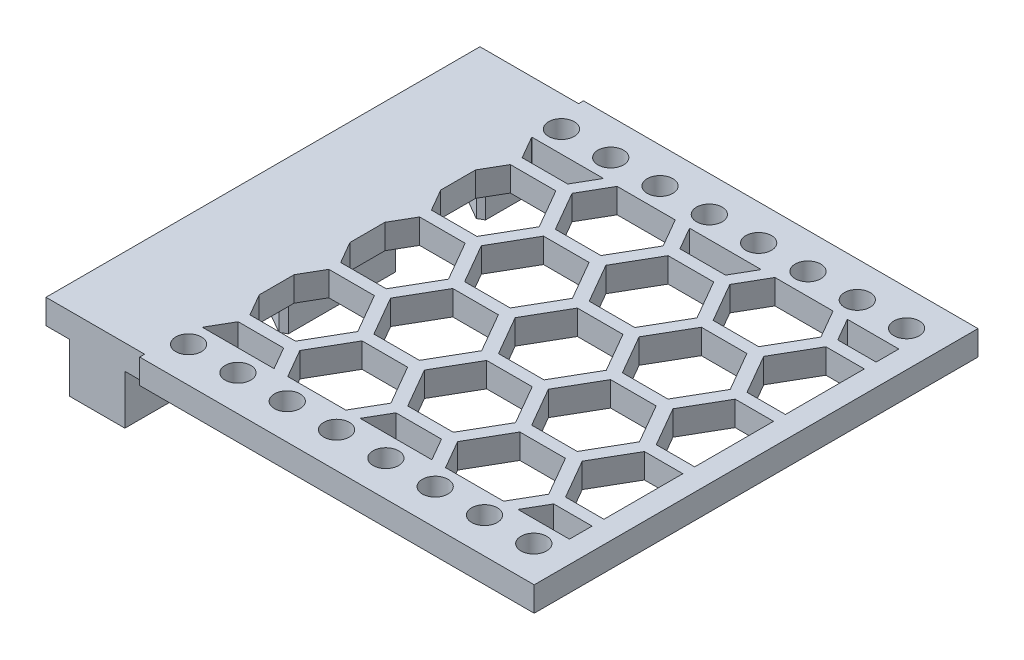
SolidWorks part; units mm, degrees
material "ABS PC"
ref_plane "Front Plane" through (0, 0, 0) normal (0, 0, 1) x (1, 0, 0)
ref_plane "Top Plane" through (0, 0, 0) normal (0, 1, 0) x (1, 0, 0)
ref_plane "Right Plane" through (0, 0, 0) normal (1, 0, 0) x (0, 0, -1)
sketch "Sketch1" plane through (0, 0, 0) normal (0, 1, 0) x (1, 0, 0)
  line L0 (0, 0) -> (-27.94, 0) construction
  line L1 (25.4, -28.575) -> (-25.4, -28.575)
  line L2 (25.4, -28.575) -> (25.4, 28.575)
  line L3 (25.4, 28.575) -> (-25.4, 28.575)
  line L4 (-25.4, -28.575) -> (-25.4, 28.575)
  line L5 (25.4, -28.575) -> (-25.4, 28.575) construction
  line L6 (25.4, 28.575) -> (-25.4, -28.575) construction
  line L7 (-38.1, -27.94) -> (-25.4, -27.94)
  line L8 (-38.1, -27.94) -> (-38.1, 27.94)
  line L9 (-38.1, 27.94) -> (-25.4, 27.94)
  line L10 (-25.4, -27.94) -> (-25.4, 27.94)
  line L11 (-27.94, -27.94) -> (-27.94, 27.94)
  point P0 (0, 0)
  point P11 (-38.1, 27.2937)
  point P12 (0, 0)
  point P13 (-38.1, 0)
  dimension "D1" = 57.15
  dimension "D2" = 50.8
  dimension "D3" = 55.88
  dimension "D4" = 12.7
  dimension "D7" = 2.54
extrude "Boss-Extrude1" add sketch "Sketch1" along normal blind 3.175 contours L4 L1 L2 L3 | L11 L7 L10 L4 L9 | L7 L11 L9 L8
sketch "Sketch2" plane through (0, 0, 0) normal (0, -1, 0) x (1, 0, 0)
  line L0 (-38.1, 27.94) -> (-38.1, -27.94) construction
  line L1 (-27.94, 6.8924) -> (-28.702, 7.3323)
  line L2 (-28.702, 7.3323) -> (-35.052, 3.6662)
  line L3 (-35.052, 3.6662) -> (-35.052, -3.6662)
  line L4 (-35.052, -3.6662) -> (-28.702, -7.3323)
  line L5 (-28.702, -7.3323) -> (-27.94, -6.8924)
  line L8 (-35.052, 27.94) -> (-35.052, 21.7338)
  line L10 (-35.052, 21.7338) -> (-28.702, 18.0677)
  line L11 (-27.94, -6.8924) -> (-27.94, 6.8924)
  line L12 (-22.352, 0) -> (-22.352, 3.6662) [skipped]
  line L13 (-28.702, 18.0677) -> (-27.94, 18.5076)
  line L14 (0, 0) -> (-38.1, 0) construction
  line L15 (-27.94, 18.5076) -> (-27.94, 27.94)
  line L17 (-27.94, -18.5076) -> (-27.94, -27.94)
  line L18 (-28.702, -18.0677) -> (-27.94, -18.5076)
  line L19 (-35.052, -21.7338) -> (-28.702, -18.0677)
  line L20 (-35.052, -27.94) -> (-35.052, -21.7338)
  line L23 (-27.94, -27.94) -> (-35.052, -27.94)
  line L24 (-35.052, 27.94) -> (-27.94, 27.94)
  line L37 (-28.702, 32.7323) -> (-35.052, 29.0662) [skipped]
  line L38 (-27.94, 32.2924) -> (-28.702, 32.7323) [skipped]
  line L39 (0, 25.4) -> (-27.94, 25.4) construction
  arc A0 (-27.94, 6.3041) -> (-27.94, -6.3041) centre (-28.702, 0) ccw construction
  arc A2 (-34.5219, -27.94) -> (-27.94, -19.0959) centre (-28.702, -25.4) cw construction
  arc A3 (-34.5219, 27.94) -> (-27.94, 19.0959) centre (-28.702, 25.4) ccw construction
  arc A5 (-27.94, 31.7041) -> (-31.877, 30.8993) centre (-28.702, 25.4) ccw construction
  dimension "D1" = 12.7
  dimension "D2" = 2
extrude "Boss-Extrude2" add sketch "Sketch2" along normal blind 6.35
sketch "Sketch3" plane through (0, 3.175, 0) normal (0, 1, 0) x (1, 0, 0)
  line L0 (25.4, -28.575) -> (-25.4, -28.575) construction
  line L1 (25.4, -28.575) -> (25.4, 28.575) construction
  line L2 (0, 0) -> (25.4, 0) construction
  circle A0 centre (20.7772, -24.003) radius 1.651
  circle A1 centre (14.4272, -24.003) radius 1.651
  circle A2 centre (8.0772, -24.003) radius 1.651
  circle A3 centre (1.7272, -24.003) radius 1.651
  circle A4 centre (-4.6228, -24.003) radius 1.651
  circle A5 centre (-10.9728, -24.003) radius 1.651
  circle A6 centre (-17.3228, -24.003) radius 1.651
  circle A7 centre (-23.6728, -24.003) radius 1.651
  circle A8 centre (-23.6728, 24.003) radius 1.651
  circle A9 centre (-17.3228, 24.003) radius 1.651
  circle A10 centre (-10.9728, 24.003) radius 1.651
  circle A11 centre (-4.6228, 24.003) radius 1.651
  circle A12 centre (1.7272, 24.003) radius 1.651
  circle A13 centre (8.0772, 24.003) radius 1.651
  circle A14 centre (14.4272, 24.003) radius 1.651
  circle A15 centre (20.7772, 24.003) radius 1.651
  dimension "D1" = 4.572
  dimension "D2" = 4.6228
  dimension "D4" = 3.302
  dimension "D3" = 8
extrude "Cut-Extrude1" cut sketch "Sketch3" against normal through all
sketch "Sketch4" plane through (0, 3.175, 0) normal (0, 1, 0) x (1, 0, 0)
  line L0 (26.4338, -0.0088) -> (23.5009, 5.0712)
  line L1 (6.1138, -0.0088) -> (3.1809, 5.0712)
  line L2 (3.1809, 5.0712) -> (-2.685, 5.0712)
  line L3 (-2.685, 5.0712) -> (-5.6179, -0.0088)
  line L4 (-5.6179, -0.0088) -> (-2.685, -5.0888)
  line L5 (-2.685, -5.0888) -> (3.1809, -5.0888)
  line L6 (3.1809, -5.0888) -> (6.1138, -0.0088)
  line L7 (23.5009, 5.0712) -> (17.635, 5.0712)
  line L8 (17.635, 5.0712) -> (14.7021, -0.0088)
  line L9 (14.7021, -0.0088) -> (17.635, -5.0888)
  line L10 (17.635, -5.0888) -> (23.5009, -5.0888)
  line L11 (23.5009, -5.0888) -> (26.4338, -0.0088)
  line L12 (26.4338, 11.6752) -> (23.5009, 16.7552)
  line L13 (23.5009, 16.7552) -> (17.635, 16.7552)
  line L14 (17.635, 16.7552) -> (14.7021, 11.6752)
  line L15 (14.7021, 11.6752) -> (17.635, 6.5952)
  line L16 (17.635, 6.5952) -> (23.5009, 6.5952)
  line L17 (23.5009, 6.5952) -> (26.4338, 11.6752)
  line L18 (26.4338, 23.3592) -> (23.5009, 28.4392)
  line L19 (23.5009, 28.4392) -> (17.635, 28.4392)
  line L20 (17.635, 28.4392) -> (14.7021, 23.3592)
  line L21 (14.7021, 23.3592) -> (17.635, 18.2792)
  line L22 (17.635, 18.2792) -> (23.5009, 18.2792)
  line L23 (23.5009, 18.2792) -> (26.4338, 23.3592)
  line L24 (6.1138, 11.6752) -> (3.1809, 16.7552)
  line L25 (3.1809, 16.7552) -> (-2.685, 16.7552)
  line L26 (-2.685, 16.7552) -> (-5.6179, 11.6752)
  line L27 (-5.6179, 11.6752) -> (-2.685, 6.5952)
  line L28 (-2.685, 6.5952) -> (3.1809, 6.5952)
  line L29 (3.1809, 6.5952) -> (6.1138, 11.6752)
  line L30 (6.1138, 23.3592) -> (3.1809, 28.4392)
  line L31 (3.1809, 28.4392) -> (-2.685, 28.4392)
  line L32 (-2.685, 28.4392) -> (-5.6179, 23.3592)
  line L33 (-5.6179, 23.3592) -> (-2.685, 18.2792)
  line L34 (-2.685, 18.2792) -> (3.1809, 18.2792)
  line L35 (3.1809, 18.2792) -> (6.1138, 23.3592)
  line L36 (-14.2062, -0.0088) -> (-17.1391, 5.0712)
  line L37 (-17.1391, 5.0712) -> (-23.005, 5.0712)
  line L38 (-23.005, 5.0712) -> (-25.9379, -0.0088)
  line L39 (-25.9379, -0.0088) -> (-23.005, -5.0888)
  line L40 (-23.005, -5.0888) -> (-17.1391, -5.0888)
  line L41 (-17.1391, -5.0888) -> (-14.2062, -0.0088)
  line L42 (-14.2062, -11.6928) -> (-17.1391, -6.6128)
  line L43 (-17.1391, -6.6128) -> (-23.005, -6.6128)
  line L44 (-23.005, -6.6128) -> (-25.9379, -11.6928)
  line L45 (-25.9379, -11.6928) -> (-23.005, -16.7728)
  line L46 (-23.005, -16.7728) -> (-17.1391, -16.7728)
  line L47 (-17.1391, -16.7728) -> (-14.2062, -11.6928)
  line L48 (-14.2062, -23.3768) -> (-17.1391, -18.2968)
  line L49 (-17.1391, -18.2968) -> (-23.005, -18.2968)
  line L50 (-23.005, -18.2968) -> (-25.9379, -23.3768)
  line L51 (-25.9379, -23.3768) -> (-23.005, -28.4568)
  line L52 (-23.005, -28.4568) -> (-17.1391, -28.4568)
  line L53 (-17.1391, -28.4568) -> (-14.2062, -23.3768)
  line L54 (6.1138, -11.6928) -> (3.1809, -6.6128)
  line L55 (3.1809, -6.6128) -> (-2.685, -6.6128)
  line L56 (-2.685, -6.6128) -> (-5.6179, -11.6928)
  line L57 (-5.6179, -11.6928) -> (-2.685, -16.7728)
  line L58 (-2.685, -16.7728) -> (3.1809, -16.7728)
  line L59 (3.1809, -16.7728) -> (6.1138, -11.6928)
  line L60 (6.1138, -23.3768) -> (3.1809, -18.2968)
  line L61 (3.1809, -18.2968) -> (-2.685, -18.2968)
  line L62 (-2.685, -18.2968) -> (-5.6179, -23.3768)
  line L63 (-5.6179, -23.3768) -> (-2.685, -28.4568)
  line L64 (-2.685, -28.4568) -> (3.1809, -28.4568)
  line L65 (3.1809, -28.4568) -> (6.1138, -23.3768)
  line L66 (-14.2062, 11.6752) -> (-17.1391, 16.7552)
  line L67 (-17.1391, 16.7552) -> (-23.005, 16.7552)
  line L68 (-23.005, 16.7552) -> (-25.9379, 11.6752)
  line L69 (-25.9379, 11.6752) -> (-23.005, 6.5952)
  line L70 (-23.005, 6.5952) -> (-17.1391, 6.5952)
  line L71 (-17.1391, 6.5952) -> (-14.2062, 11.6752)
  line L72 (-14.2062, 23.3592) -> (-17.1391, 28.4392)
  line L73 (-17.1391, 28.4392) -> (-23.005, 28.4392)
  line L74 (-23.005, 28.4392) -> (-25.9379, 23.3592)
  line L75 (-25.9379, 23.3592) -> (-23.005, 18.2792)
  line L76 (-23.005, 18.2792) -> (-17.1391, 18.2792)
  line L77 (-17.1391, 18.2792) -> (-14.2062, 23.3592)
  line L78 (26.4338, -11.6928) -> (23.5009, -6.6128)
  line L79 (16.2325, -17.5348) -> (13.2995, -12.4548)
  line L80 (13.2995, -12.4548) -> (7.4336, -12.4548)
  line L81 (7.4336, -12.4548) -> (4.5007, -17.5348)
  line L82 (4.5007, -17.5348) -> (7.4336, -22.6148)
  line L83 (7.4336, -22.6148) -> (13.2995, -22.6148)
  line L84 (13.2995, -22.6148) -> (16.2325, -17.5348)
  line L85 (23.5009, -6.6128) -> (17.635, -6.6128)
  line L86 (17.635, -6.6128) -> (14.7021, -11.6928)
  line L87 (14.7021, -11.6928) -> (17.635, -16.7728)
  line L88 (17.635, -16.7728) -> (23.5009, -16.7728)
  line L89 (23.5009, -16.7728) -> (26.4338, -11.6928)
  line L90 (26.4338, -23.3768) -> (23.5009, -18.2968)
  line L91 (23.5009, -18.2968) -> (17.635, -18.2968)
  line L92 (17.635, -18.2968) -> (14.7021, -23.3768)
  line L93 (14.7021, -23.3768) -> (17.635, -28.4568)
  line L94 (17.635, -28.4568) -> (23.5009, -28.4568)
  line L95 (23.5009, -28.4568) -> (26.4338, -23.3768)
  line L96 (-4.0875, -17.5348) -> (-7.0205, -12.4548)
  line L97 (-12.8864, -12.4548) -> (-15.8193, -17.5348)
  line L98 (-15.8193, -17.5348) -> (-12.8864, -22.6148)
  line L99 (-7.0205, -22.6148) -> (-4.0875, -17.5348)
  line L100 (-7.0205, -12.4548) -> (-12.8864, -12.4548)
  line L101 (-12.8864, -22.6148) -> (-7.0205, -22.6148)
  line L102 (-4.0875, -5.8508) -> (-7.0205, -0.7708)
  line L103 (-12.8864, -0.7708) -> (-15.8193, -5.8508)
  line L104 (-15.8193, -5.8508) -> (-12.8864, -10.9308)
  line L105 (-7.0205, -10.9308) -> (-4.0875, -5.8508)
  line L106 (-7.0205, -0.7708) -> (-12.8864, -0.7708)
  line L107 (-12.8864, -10.9308) -> (-7.0205, -10.9308)
  line L108 (-4.0875, 5.8332) -> (-7.0205, 10.9132)
  line L109 (-12.8864, 10.9132) -> (-15.8193, 5.8332)
  line L110 (-15.8193, 5.8332) -> (-12.8864, 0.7532)
  line L111 (-7.0205, 0.7532) -> (-4.0875, 5.8332)
  line L112 (-7.0205, 10.9132) -> (-12.8864, 10.9132)
  line L113 (-12.8864, 0.7532) -> (-7.0205, 0.7532)
  line L114 (-4.0875, 17.5172) -> (-7.0205, 22.5972)
  line L115 (-12.8864, 22.5972) -> (-15.8193, 17.5172)
  line L116 (-15.8193, 17.5172) -> (-12.8864, 12.4372)
  line L117 (-7.0205, 12.4372) -> (-4.0875, 17.5172)
  line L118 (-7.0205, 22.5972) -> (-12.8864, 22.5972)
  line L119 (-12.8864, 12.4372) -> (-7.0205, 12.4372)
  line L120 (16.2325, -5.8508) -> (13.2995, -0.7708)
  line L121 (7.4336, -0.7708) -> (4.5007, -5.8508)
  line L122 (4.5007, -5.8508) -> (7.4336, -10.9308)
  line L123 (13.2995, -10.9308) -> (16.2325, -5.8508)
  line L124 (13.2995, -0.7708) -> (7.4336, -0.7708)
  line L125 (7.4336, -10.9308) -> (13.2995, -10.9308)
  line L126 (16.2325, 5.8332) -> (13.2995, 10.9132)
  line L127 (7.4336, 10.9132) -> (4.5007, 5.8332)
  line L128 (4.5007, 5.8332) -> (7.4336, 0.7532)
  line L129 (13.2995, 0.7532) -> (16.2325, 5.8332)
  line L130 (13.2995, 10.9132) -> (7.4336, 10.9132)
  line L131 (7.4336, 0.7532) -> (13.2995, 0.7532)
  line L132 (16.2325, 17.5172) -> (13.2995, 22.5972)
  line L133 (7.4336, 22.5972) -> (4.5007, 17.5172)
  line L134 (4.5007, 17.5172) -> (7.4336, 12.4372)
  line L135 (13.2995, 12.4372) -> (16.2325, 17.5172)
  line L136 (13.2995, 22.5972) -> (7.4336, 22.5972)
  line L137 (7.4336, 12.4372) -> (13.2995, 12.4372)
  line L138 (-24.642, 21.2002) -> (22.58, 21.2002)
  line L139 (22.58, 21.2002) -> (22.58, -21.2178)
  line L140 (22.58, -21.2178) -> (-24.642, -21.2178)
  line L141 (-24.642, -21.2178) -> (-24.642, 21.2002)
  circle A0 centre (0.2479, -0.0088) radius 5.08 construction
  circle A1 centre (20.5679, -0.0088) radius 5.08 construction
  circle A2 centre (20.5679, 11.6752) radius 5.08 construction
  circle A3 centre (20.5679, 23.3592) radius 5.08 construction
  circle A4 centre (0.2479, 11.6752) radius 5.08 construction
  circle A5 centre (0.2479, 23.3592) radius 5.08 construction
  circle A6 centre (-20.0721, -0.0088) radius 5.08 construction
  circle A7 centre (-20.0721, -11.6928) radius 5.08 construction
  circle A8 centre (-20.0721, -23.3768) radius 5.08 construction
  circle A9 centre (0.2479, -11.6928) radius 5.08 construction
  circle A10 centre (0.2479, -23.3768) radius 5.08 construction
  circle A11 centre (-20.0721, 11.6752) radius 5.08 construction
  circle A12 centre (-20.0721, 23.3592) radius 5.08 construction
  circle A13 centre (10.3666, -17.5348) radius 5.08 construction
  circle A14 centre (20.5679, -11.6928) radius 5.08 construction
  circle A15 centre (20.5679, -23.3768) radius 5.08 construction
  circle A16 centre (-9.9534, -17.5348) radius 5.08 construction
  circle A17 centre (-9.9534, -5.8508) radius 5.08 construction
  circle A18 centre (-9.9534, 5.8332) radius 5.08 construction
  circle A19 centre (-9.9534, 17.5172) radius 5.08 construction
  circle A20 centre (10.3666, -5.8508) radius 5.08 construction
  circle A21 centre (10.3666, 5.8332) radius 5.08 construction
  circle A22 centre (10.3666, 17.5172) radius 5.08 construction
  dimension "D1" = 10.16
  dimension "D2" = 1.524
  dimension "D3" = 1.524
extrude "Cut-Extrude2" cut sketch "Sketch4" against normal through all contours L139 L138 L21 L22 | L138 L133 L134 L137 L135 L132 | L138 L33 L34 L35 | L138 L115 L116 L119 L117 L114 | L141 L75 L76 L77 L138 | L141 L69 L70 L71 L66 L67 L68 | L141 L39 L40 L41 L36 L37 L38 | L141 L45 L46 L47 L42 L43 L44 | L141 L140 L48 L49 L50 | L140 L99 L96 L100 L97 L98 | L140 L60 L61 L62 | L140 L84 L79 L80 L81 L82 | L140 L139 L91 L92 | L139 L85 L86 L87 L88 | L139 L7 L8 L9 L10 | L139 L13 L14 L15 L16 | L128 L131 L129 L126 L130 L127 | L28 L29 L24 L25 L26 L27 | L5 L6 L1 L2 L3 L4 | L122 L125 L123 L120 L124 L121 | L58 L59 L54 L55 L56 L57 | L104 L107 L105 L102 L106 L103 | L110 L113 L111 L108 L112 L109
